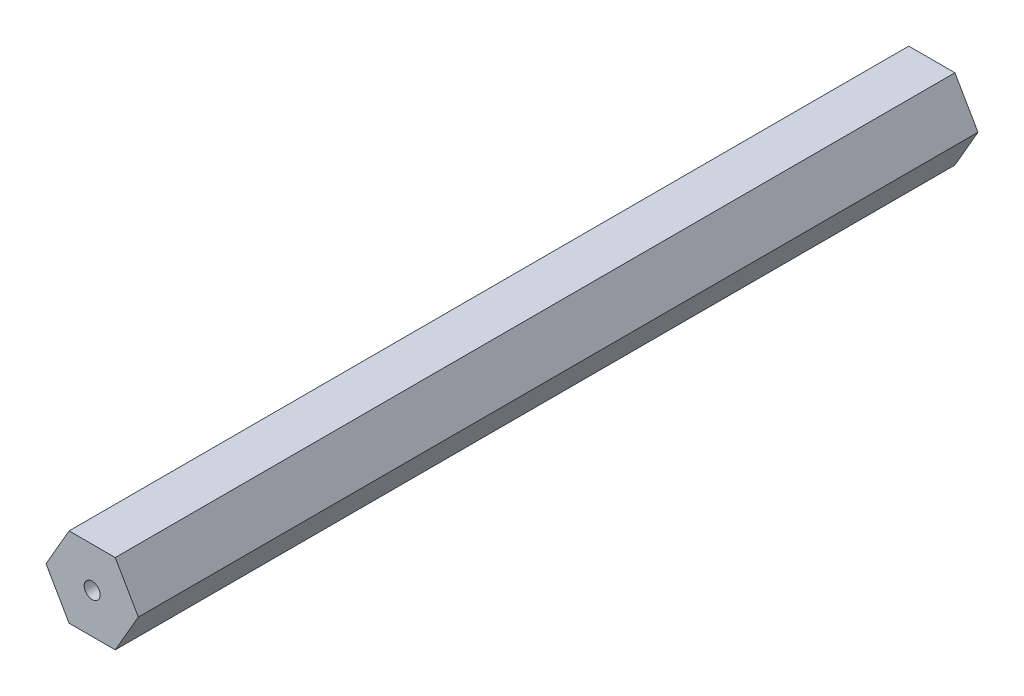
SolidWorks part; units mm, degrees
material "1060 Alloy"
ref_plane "Front Plane" through (0, 0, 0) normal (0, 0, 1) x (1, 0, 0)
ref_plane "Top Plane" through (0, 0, 0) normal (0, 1, 0) x (1, 0, 0)
ref_plane "Right Plane" through (0, 0, 0) normal (1, 0, 0) x (0, 0, -1)
sketch "Sketch1" plane through (0, 0, 0) normal (0, 0, 1) x (1, 0, 0)
  line L1 (7.3323, 0) -> (3.6662, 6.35)
  line L2 (3.6662, 6.35) -> (-3.6662, 6.35)
  line L3 (-3.6662, 6.35) -> (-7.3323, 0)
  line L4 (-7.3323, 0) -> (-3.6662, -6.35)
  line L5 (-3.6662, -6.35) -> (3.6662, -6.35)
  line L6 (3.6662, -6.35) -> (7.3323, 0)
  circle A0 centre (0, 0) radius 1.27
  circle A1 centre (0, 0) radius 6.35 construction
  dimension "D1" = 12.7
  dimension "D2" = 2.54
extrude "Boss-Extrude1" add sketch "Sketch1" along normal blind 133.35
